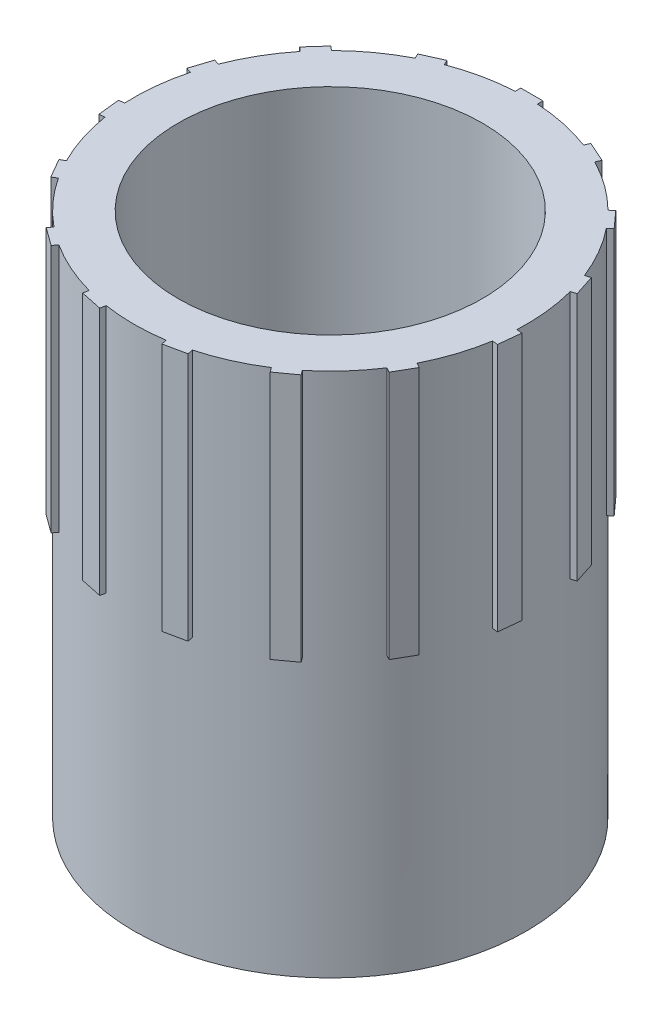
SolidWorks part; units mm, degrees
ref_plane "Front Plane" through (0, 0, 0) normal (0, 0, 1) x (1, 0, 0)
ref_plane "Top Plane" through (0, 0, 0) normal (0, 1, 0) x (1, 0, 0)
ref_plane "Right Plane" through (0, 0, 0) normal (1, 0, 0) x (0, 0, -1)
sketch "Sketch1" plane through (0, 0, 0) normal (0, 1, 0) x (1, 0, 0)
  circle A0 centre (0, 0) radius 3.55
  dimension "D1" = 7.1
extrude "Body" add sketch "Sketch1" along normal blind 9.5
sketch "Sketch2" plane through (0, 9.5, 0) normal (0, 1, 0) x (1, 0, 0)
  line L2 (-0.2, 3.5444) -> (-0.2, 3.6444)
  line L3 (-0.2, 3.6444) -> (0.2, 3.6444)
  line L4 (0.2, 3.5444) -> (0.2, 3.6444)
  circle A0 centre (0, 0) radius 3.55 construction
  arc A1 (0.2, 3.5444) -> (-0.2, 3.5444) centre (0, 0) ccw
  dimension "D1" = 0.1
  dimension "D2" = 0.2
  dimension "D3" = 0.4
extrude "Teeth" add sketch "Sketch2" against normal offset from surface (4.5 mm away) 5 up to face at (0, 0, 3.55)
pattern_circular "CirPattern1" count 15 over 360 about axis through (0, 0, 0) along (0, 1, 0) of "Teeth"
hole_wizard "M5 Clearance Hole1" positions "Sketch3" profile "Sketch4" hole size "M5" standard "ANSI Metric" end condition through all
sketch "Sketch3" plane through (0, 9.5, 0) normal (0, 1, 0) x (1, 0, 0)
  point P0 (0, 0)
sketch "Sketch4" plane through (0, 9.5, 0) normal (1, 0, 0) x (0, 0, 1)
  line L0 (0, 0) -> (0, 9.5)
  line L1 (0, 9.5) -> (2.75, 9.5)
  line L2 (2.75, 9.5) -> (2.75, 0)
  line L5 (2.75, 0) -> (0, 0)
  line L11 (0, -6.35) -> (0, 107.95) construction
  dimension "Thru Hole Dia." = 5.5
  dimension "Thru Hole Depth" = 9.5
